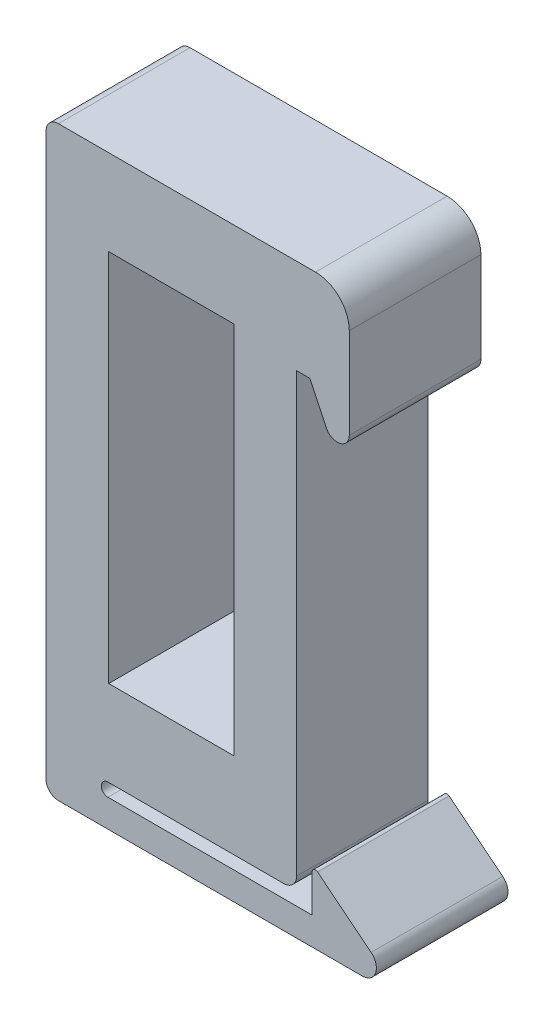
SolidWorks part; units mm, degrees
ref_plane "Front Plane" through (0, 0, 0) normal (0, 0, 1) x (1, 0, 0)
ref_plane "Top Plane" through (0, 0, 0) normal (0, 1, 0) x (1, 0, 0)
ref_plane "Right Plane" through (0, 0, 0) normal (1, 0, 0) x (0, 0, -1)
sketch "Sketch1" plane through (0, 0, 0) normal (0, 0, 1) x (1, 0, 0)
  line L4 (52.3488, 18.6668) -> (52.3488, 11.7814)
  line L11 (34.0689, -13.6945) -> (43.5863, -13.6945)
  line L14 (34.0689, -13.6945) -> (34.0689, 14.7245)
  line L15 (48.3488, 14.0314) -> (49.3488, 14.0314)
  line L16 (49.5312, -21.2062) -> (49.5312, -18.3535)
  line L17 (34.0689, 14.7245) -> (43.5863, 14.7245)
  line L18 (43.5863, -13.6945) -> (43.5863, 14.7245)
  line L19 (48.3488, -19.2262) -> (48.3488, 14.0314)
  line L20 (34.0689, -13.6945) -> (43.5863, 14.7245) construction
  line L21 (34.0689, 14.7245) -> (43.5863, -13.6945) construction
  line L22 (49.5312, -21.2062) -> (34.0066, -21.2062)
  line L23 (34.0066, -20.2062) -> (47.3688, -20.2062)
  line L24 (53.343, -23.3096) -> (30.2464, -23.3096)
  line L25 (29.3064, -22.3696) -> (29.3064, 20.2945)
  line L27 (54.0078, -21.4146) -> (49.9373, -18.1583)
  line L28 (49.3488, 14.0314) -> (50.6107, 11.3878)
  line L34 (49.7812, 21.2345) -> (30.2464, 21.2345)
  arc A4 (50.6107, 11.3878) -> (52.3488, 11.7814) centre (51.4352, 11.7814) ccw
  arc A5 (47.3688, -20.2062) -> (48.3488, -19.2262) centre (47.3688, -19.2262) ccw
  arc A6 (34.0066, -20.2062) -> (34.0066, -21.2062) centre (34.0066, -20.7062) ccw
  arc A7 (49.5312, -18.3535) -> (49.9373, -18.1583) centre (49.7812, -18.3535) cw
  arc A8 (53.343, -23.3096) -> (54.0078, -21.4146) centre (53.343, -22.2455) ccw
  arc A11 (49.7812, 21.2345) -> (52.3488, 18.6668) centre (49.7812, 18.6668) cw
  arc A12 (30.2464, -23.3096) -> (29.3064, -22.3696) centre (30.2464, -22.3696) cw
  arc A13 (29.3064, 20.2945) -> (30.2464, 21.2345) centre (30.2464, 20.2945) cw
  point P2 (0, 0)
  point P11 (49.8925, -19.2999)
  point P18 (48.3488, -2.5974)
  point P19 (29.3064, -1.0376)
  point P31 (49.7812, -19.2935)
  point P35 (0, 0)
  dimension "D5" = 0.94
  dimension "D6" = 0.94
extrude "Boss-Extrude2" add sketch "Sketch1" along normal blind 10
sketch "Sketch4" plane through (29.3064, 0, 0) normal (-1, 0, 0) x (0, 0, 1)
  line L0 (10, -1.0376) -> (0, -1.0376)
  line L1 (10, 20.2945) -> (10, -22.3696) construction
  line L2 (0, 20.2945) -> (0, -22.3696) construction
  line L3 (4.549, -1.0376) -> (4.549, -17.5376)
  line L4 (4.549, -17.5376) -> (10, -17.5376)
  line L5 (4.549, -1.0376) -> (4.549, 17.4624)
  circle A0 centre (4.549, 17.4624) radius 1.1389
  circle A3 centre (4.5511, -17.5401) radius 1.1389
  point P11 (0, 0)
extrude "Cut-Extrude4" cut sketch "Sketch4" against normal blind 10
